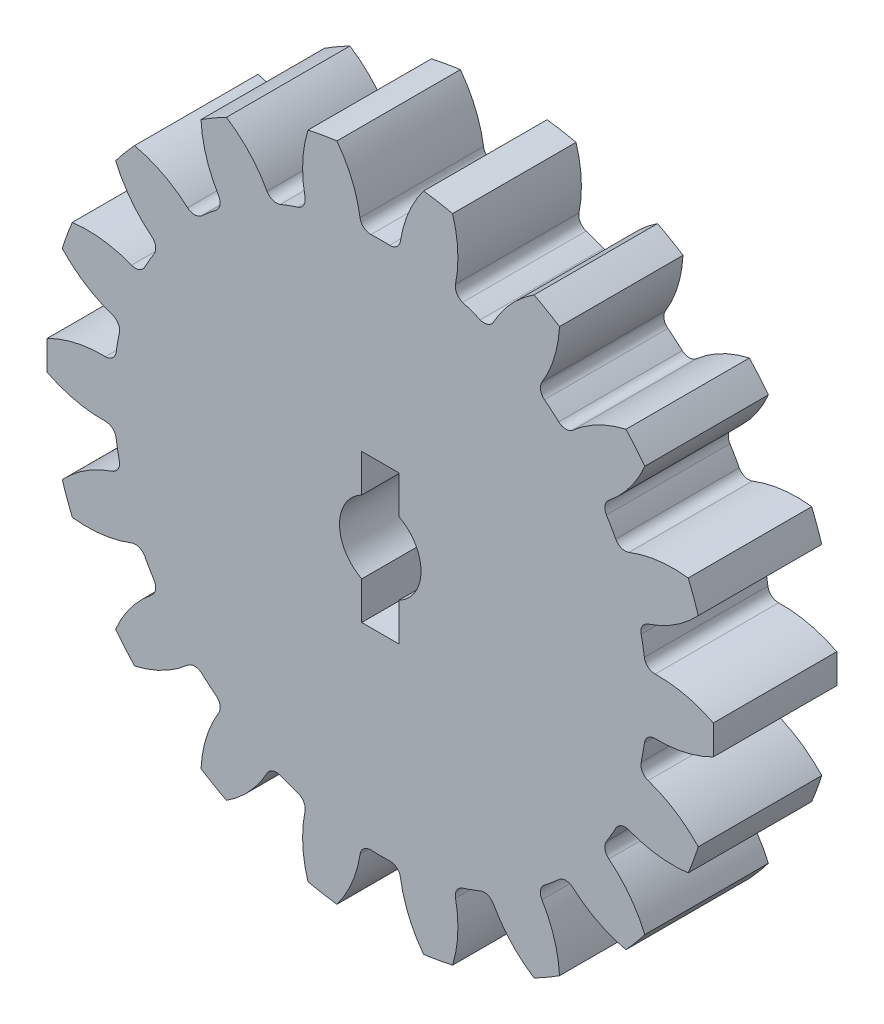
SolidWorks part; units mm, degrees
ref_plane "Front" through (0, 0, 0) normal (0, 0, 1) x (1, 0, 0)
ref_plane "Top" through (0, 0, 0) normal (0, 1, 0) x (1, 0, 0)
ref_plane "Right" through (0, 0, 0) normal (1, 0, 0) x (0, 0, -1)
sketch "Sketch1" plane through (0, 0, 0) normal (0, 0, 1) x (1, 0, 0)
  circle A0 centre (0, 0) radius 10.8
  circle A1 centre (0, 0) radius 13.5
  circle A2 centre (0, 0) radius 12.15
  dimension "D1" = 27
  dimension "D2" = 21.6
  dimension "D3" = 24.3
extrude "Boss-Extrude1" add sketch "Sketch1" along normal mid plane 5 contours A1
sketch "Sketch3" plane through (0, 0, 0) normal (0, 0, 1) x (1, 0, 0)
  line L0 (0, 0) -> (0, 13.5) construction
  line L1 (0, 0) -> (-0.7745, 10.7722) construction
  line L2 (-1.0589, 12.1038) -> (1.0589, 12.1038) construction
  line L3 (-1.5353, 13.4124) -> (0, 9.1943) construction
  line L4 (1.0589, 12.1038) -> (3.1447, 11.736) construction
  line L5 (2.3443, 13.2949) -> (0, 0) construction
  arc A0 (-0.7745, 10.7722) -> (0.7745, 10.7722) centre (0, 0) cw
  arc A4 (1.7552, 13.3854) -> (-1.7552, 13.3854) centre (0, 0) ccw
  circle A5 centre (0, 0) radius 13.5 construction
  arc A7 (-1.7552, 13.3854) -> (-0.7745, 10.7722) centre (-5.6881, 10.4189) cw
  arc A10 (1.7552, 13.3854) -> (0.7745, 10.7722) centre (5.6881, 10.4189) ccw
  circle A11 centre (0, 0) radius 10.8 construction
  circle A12 centre (0, 0) radius 12.15 construction
  dimension "D1" = 20
  dimension "D2" = 10
extrude "Cut-Extrude1" cut sketch "Sketch3" against normal through all both and the other way through all contours A10 A4 A7 A0
fillet "Fillet2" radius 0.43 2 edges at (-0.7745, 10.7722, 0) (0.7745, 10.7722, 0)
pattern_circular "CirPattern1" count 18 over 360 about axis through (0, 0, 0) along (0, 0, 1) of "Cut-Extrude1", "Fillet2"
sketch "Sketch4" plane through (0, 0, 0) normal (0, 0, 1) x (1, 0, 0)
  line L0 (-0.75, 3) -> (0.75, 3)
  line L1 (-0.75, -3) -> (0.75, -3) construction
  line L3 (-0.75, 3) -> (0.75, 3) construction
  line L7 (0.75, 3) -> (0.75, 1.4697)
  line L8 (-0.75, 3) -> (-0.75, 1.4697)
  line L9 (-0.75, -1.4697) -> (-0.75, -3)
  line L10 (-0.75, -3) -> (0.75, -3)
  line L11 (0.75, -3) -> (0.75, -1.4697)
  arc A1 (-0.75, 1.4697) -> (-0.75, -1.4697) centre (0, 0) ccw
  arc A2 (0.75, 1.4697) -> (0.75, -1.4697) centre (0, 0) cw
  dimension "D1" = 1.65
  dimension "D4" = 1.65
  dimension "D2" = 6
  dimension "D3" = 1.5
  dimension "D5" = 1.5
  dimension "D6" = 1.5303
extrude "Through_Center_Hole" cut sketch "Sketch4" against normal through all both and the other way through all
sketch "Sketch5" plane through (0, 0, 2.5) normal (0, 0, 1) x (1, 0, 0)
  circle A0 centre (0, 0) radius 1.65
  dimension "D1" = 3.3
equation "\"od\"= 27'outside diameter"
equation "\"n\"= 18'number of teeth"
equation "\"m\"= \"od\" / ( \"n\" + 2 )'module"
equation "\"p\"= \"m\" * pi'pitch"
equation "\"d\"= \"m\" * \"n\"'primitive diameter"
equation "\"da\"= \"d\" + 2 * \"m\"'head diamater"
equation "\"df\"= \"d\" - 2 * \"m\"'foot diameter"
equation "\"D1@Sketch1\"=\"od\""
equation "\"D2@Sketch1\"=\"df\""
equation "\"D3@Sketch1\"=\"d\""
equation "\"D2@Sketch3\"=180/\"n\""
equation "\"D1@CirPattern1\"=\"n\""
